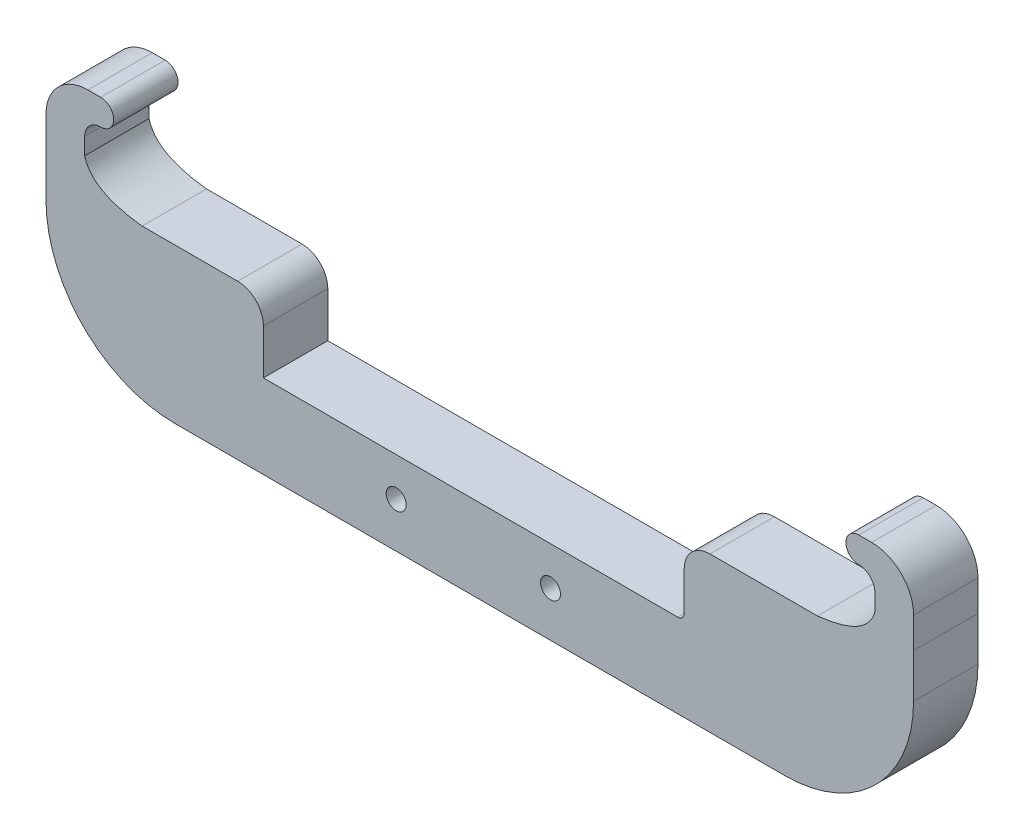
SolidWorks part; units mm, degrees
ref_plane "Płaszczyzna przednia" through (0, 0, 0) normal (0, 0, 1) x (1, 0, 0)
ref_plane "Płaszczyzna górna" through (0, 0, 0) normal (0, 1, 0) x (1, 0, 0)
ref_plane "Płaszczyzna prawa" through (0, 0, 0) normal (1, 0, 0) x (0, 0, -1)
sketch "Szkic1" plane through (0, 0, 0) normal (0, 0, 1) x (1, 0, 0)
  line L0 (650.1352, -439.2962) -> (667.4978, -439.2962)
  line L1 (552.8031, -407.6962) -> (552.8031, -412.4993)
  line L2 (586.5551, -426.2962) -> (586.5551, -419.2962)
  line L3 (687.4924, -407.6962) -> (687.4924, -412.4993)
  line L4 (650.1352, -439.2962) -> (588.3051, -439.2962)
  line L5 (678.9924, -401.1962) -> (680.9924, -401.1962)
  line L6 (567.725, -415.2962) -> (582.5551, -415.2962)
  line L7 (586.5551, -426.2962) -> (647.8852, -426.2962)
  line L8 (651.8852, -425.2962) -> (651.8852, -419.2962)
  line L9 (681.4924, -407.6962) -> (681.4924, -410.3096)
  line L12 (672.5705, -415.2962) -> (655.8852, -415.2962)
  line L13 (687.4978, -419.2962) -> (687.4924, -412.4993)
  line L20 (558.8031, -407.6962) -> (558.8031, -410.3096)
  line L23 (647.8852, -426.2962) -> (650.8852, -426.2962)
  line L24 (588.3051, -439.2962) -> (572.8031, -439.2962)
  line L27 (552.8031, -412.4993) -> (552.8031, -419.2962)
  line L30 (561.3031, -401.1962) -> (559.3031, -401.1962)
  line L31 (559.3031, -401.1962) -> (559.3284, -401.1872)
  arc A0 (559.3031, -401.1962) -> (552.8031, -407.6962) centre (559.3031, -407.6962) ccw
  arc A1 (561.3031, -405.1962) -> (561.3031, -401.1962) centre (561.3031, -403.1962) ccw
  arc A2 (582.5551, -415.2962) -> (586.5551, -419.2962) centre (582.5551, -419.2962) cw
  arc A3 (687.4978, -419.2962) -> (667.4978, -439.2962) centre (667.4978, -419.2962) cw
  arc A4 (558.8031, -407.6962) -> (561.3031, -405.1962) centre (561.3031, -407.6962) cw
  arc A5 (655.8852, -415.2962) -> (651.8852, -419.2962) centre (655.8852, -419.2962) ccw
  arc A6 (650.8852, -426.2962) -> (651.8852, -425.2962) centre (650.8852, -425.2962) ccw
  arc A7 (552.8031, -419.2962) -> (572.8031, -439.2962) centre (572.8031, -419.2962) ccw
  arc A8 (680.9924, -401.1962) -> (687.4924, -407.6962) centre (680.9924, -407.6962) cw
  arc A9 (678.9924, -405.1962) -> (678.9924, -401.1962) centre (678.9924, -403.1962) cw
  arc A10 (681.4924, -407.6962) -> (678.9924, -405.1962) centre (678.9924, -407.6962) ccw
  spline S0 degree 2 poles (567.725, -415.2962) (559.9563, -414.4634) (558.8031, -410.3096) knots 0 0 0 0.645202 0.645202 0.645202
  spline S1 degree 2 poles (672.5705, -415.2962) (680.3393, -414.4634) (681.4924, -410.3096) knots 0 0 0 0.645202 0.645202 0.645202
  point P0 (567.8031, -401.1962)
  point P20 (567.8031, -405.1962)
  point P21 (559.3031, -405.1962)
  point P30 (679.1031, -405.1962)
  point P31 (670.6031, -405.1962)
  point P45 (650.1352, -433.2962)
  dimension "D9" = 13
  dimension "D3" = 20
  dimension "D7" = 1
  dimension "D5" = 20
  dimension "D8" = 4
  dimension "D1" = 4
  dimension "D4" = 6
extrude "Dodanie-wyciągnięcie1" add sketch "Szkic1" along normal blind 10 contours L30 A1 A4 L20 S0 L6 A2 L2 L7 L23 A6 L8 A5 L12 S1 L9 A10 A9 L5 A8 L3 L13 A3 L0 L4 L24 A7 L27 L1 A0
sketch "Szkic2" plane through (0, 0, 10) normal (0, 0, 1) x (1, 0, 0)
  circle A0 centre (631.1301, -432.2962) radius 1.55 construction
  circle A1 centre (607.1641, -432.2962) radius 1.55 construction
  circle A2 centre (631.1301, -432.2962) radius 1.55
  circle A3 centre (607.1641, -432.2962) radius 1.55
extrude "Wytnij-wyciągnięcie1" cut sketch "Szkic2" against normal blind 10
equation "\"tolerancja_wpusy\"=0.2"
equation "\"dlugosc_wpustu_duzy\"=20"
equation "\"srednica_otworu_M3\"=3.1"
equation "\"szerokosc_nogi_T\"=3.1"
equation "\"dlugosc_T_30\"=11"
equation "\"grubosc_na_nakretke_kwadrat\"=2"
equation "\"szerokosc_na_nakretke_kwadrat\"=5.85"
equation "\"wyokosc_nadstawki_T\"=0.5"
equation "\"dlugosc_T_20_6\"=14"
